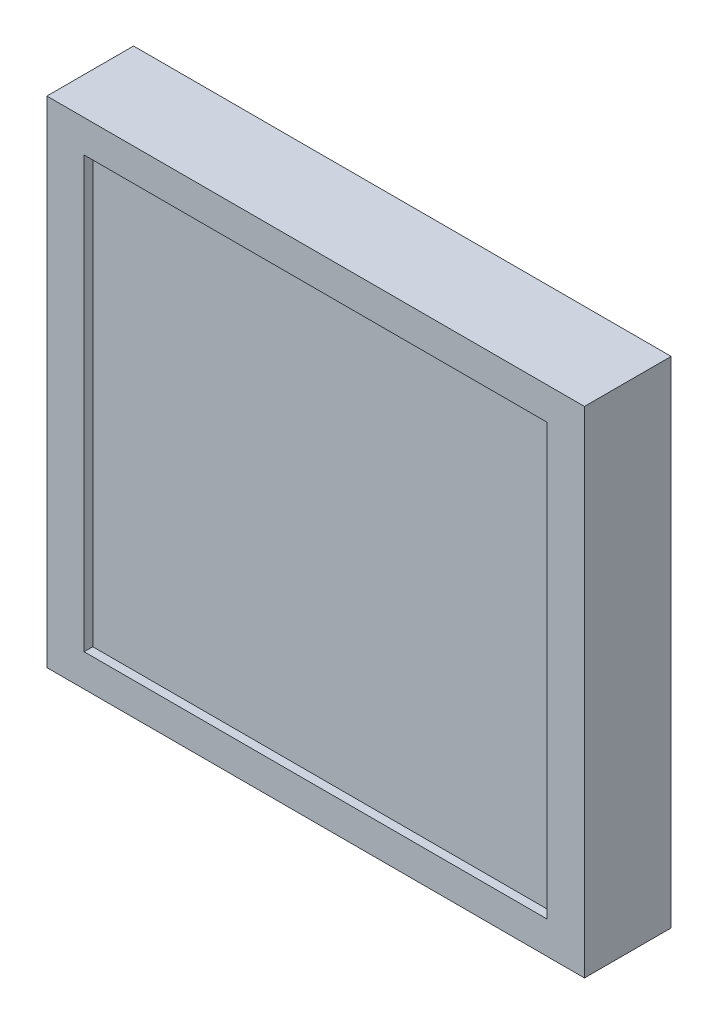
SolidWorks part; units mm, degrees
ref_plane "前视基准面" through (0, 0, 0) normal (0, 0, 1) x (1, 0, 0)
ref_plane "上视基准面" through (0, 0, 0) normal (0, 1, 0) x (1, 0, 0)
ref_plane "右视基准面" through (0, 0, 0) normal (1, 0, 0) x (0, 0, -1)
other "Configuration Table"
sketch "草图1" plane through (0, 0, 0) normal (0, 0, 1) x (1, 0, 0)
  line L1 (-6.2017, -5.7103) -> (6.2017, -5.7103)
  line L2 (-6.2017, -5.7103) -> (-6.2017, 5.7103)
  line L3 (-6.2017, 5.7103) -> (6.2017, 5.7103)
  line L4 (6.2017, -5.7103) -> (6.2017, 5.7103)
  line L5 (-6.2017, -5.7103) -> (6.2017, 5.7103) construction
  line L6 (-6.2017, 5.7103) -> (6.2017, -5.7103) construction
  point P0 (0, 0)
extrude "凸台-拉伸1" add sketch "草图1" along normal blind 2
sketch "草图2" plane through (0, 0, 2) normal (0, 0, 1) x (1, 0, 0)
  line L1 (-5.3418, -4.9631) -> (5.3418, -4.9631)
  line L2 (-5.3418, -4.9631) -> (-5.3418, 4.9631)
  line L3 (-5.3418, 4.9631) -> (5.3418, 4.9631)
  line L4 (5.3418, -4.9631) -> (5.3418, 4.9631)
  line L5 (-5.3418, -4.9631) -> (5.3418, 4.9631) construction
  line L6 (-5.3418, 4.9631) -> (5.3418, -4.9631) construction
  point P0 (0, 0)
extrude "切除-拉伸1" cut sketch "草图2" against normal blind 0.2
